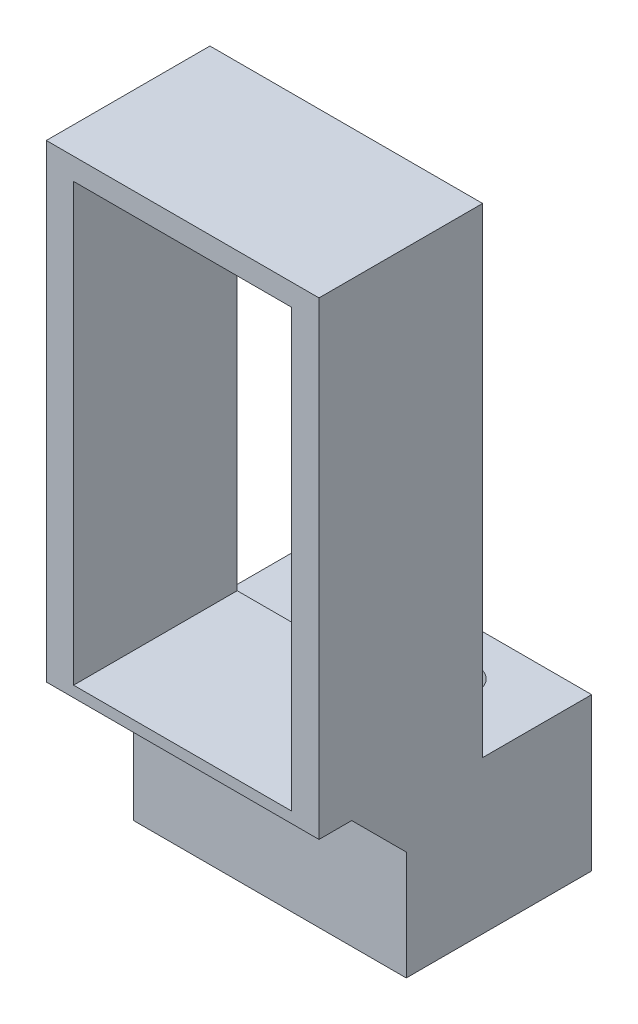
SolidWorks part; units mm, degrees
ref_plane "Plan de face" through (0, 0, 0) normal (0, 0, 1) x (1, 0, 0)
ref_plane "Plan de dessus" through (0, 0, 0) normal (0, 1, 0) x (1, 0, 0)
ref_plane "Plan de droite" through (0, 0, 0) normal (1, 0, 0) x (0, 0, -1)
sketch "Esquisse1" plane through (0, 0, 0) normal (0, 1, 0) x (1, 0, 0)
  line L0 (12.5, 0) -> (0, 0)
  line L1 (12.5, 0) -> (12.5, 12.5)
  line L2 (12.5, 12.5) -> (-12.5, 12.5)
  line L3 (-12.5, 12.5) -> (-12.5, -12.5)
  line L4 (-12.5, -12.5) -> (12.5, -12.5)
  line L5 (12.5, -12.5) -> (12.5, 0)
  dimension "D1" = 12.5
  dimension "D2" = 25
  dimension "D3" = 12.5
  dimension "D4" = 25
extrude "Boss.-Extru.1" add sketch "Esquisse1" along normal blind 14
sketch "Esquisse2" plane through (0, 0, 12.5) normal (0, 0, 1) x (1, 0, 0)
  line L0 (-12.5, 14) -> (12.5, 14)
  line L1 (12.5, 14) -> (12.5, 16.5)
  line L2 (12.5, 16.5) -> (12.5, 58)
  line L3 (12.5, 58) -> (-12.5, 58)
  line L4 (-12.5, 58) -> (-12.5, 14)
  line L5 (-12.5, 58) -> (-12.5, 56) construction
  line L6 (-12.5, 56) -> (-10, 56) construction
  line L7 (-10, 56) -> (-10, 16)
  line L8 (-10, 56) -> (10, 56)
  line L9 (10, 56) -> (10, 16)
  line L10 (10, 16) -> (-10, 16)
  dimension "D1" = 2.5
  dimension "D2" = 2.5
  dimension "D3" = 2
  dimension "D4" = 25
  dimension "D5" = 20
  dimension "D6" = 40
  dimension "D7" = 41.5
extrude "Boss.-Extru.2" add sketch "Esquisse2" against normal blind 15
sketch "Esquisse3" plane through (-12.5, 0, 0) normal (-1, 0, 0) x (0, 0, 1)
  line L0 (12.5, 0) -> (4.5, 0)
  line L1 (-12.5, 0) -> (12.5, 0) construction
  line L2 (12.5, 0) -> (12.5, 15)
  line L3 (12.5, 58) -> (12.5, 0) construction
  line L4 (12.5, 15) -> (9.5, 15)
  line L5 (9.5, 15) -> (9.5, 10) construction
  line L6 (9.5, 10) -> (4.5, 10) construction
  line L7 (4.5, 10) -> (9.5, 15)
  line L8 (4.5, 10) -> (4.5, 0)
  dimension "D1" = 8
  dimension "D2" = 15
  dimension "D3" = 3
  dimension "D4" = 10
extrude "Enlèv. mat.-Extru.1" cut sketch "Esquisse3" against normal up to next
sketch "Esquisse4" plane through (0, 14, 0) normal (0, 1, 0) x (1, 0, 0)
  line L0 (0, 2.5) -> (0, 12.5) construction
  line L2 (-12.5, 2.5) -> (12.5, 2.5) construction
  line L3 (12.5, 12.5) -> (-12.5, 12.5) construction
  line L4 (0, 7.5) -> (5, 7.5) construction
  line L5 (0, 7.5) -> (-5, 7.5) construction
  circle A0 centre (5, 7.5) radius 2
  circle A1 centre (-5, 7.5) radius 2
  dimension "D1" = 5
  dimension "D2" = 5
  dimension "D3" = 10
extrude "Enlèv. mat.-Extru.2" cut sketch "Esquisse4" against normal up to next
